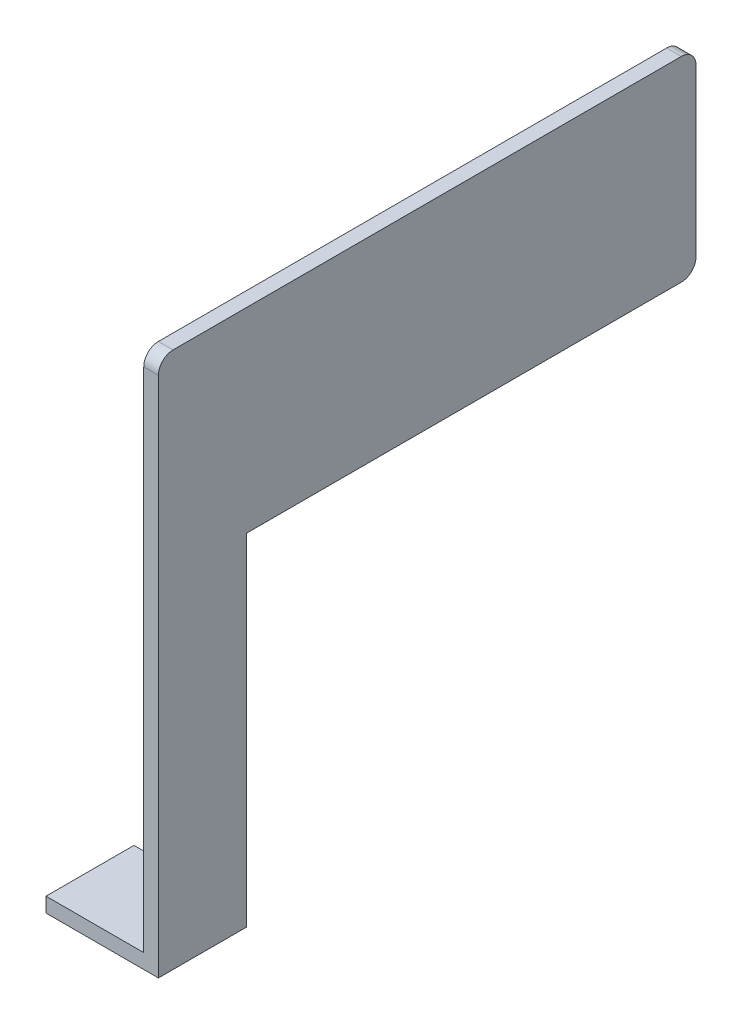
SolidWorks part; units mm, degrees
ref_plane "前视基准面" through (0, 0, 0) normal (0, 0, 1) x (1, 0, 0)
ref_plane "上视基准面" through (0, 0, 0) normal (0, 1, 0) x (1, 0, 0)
ref_plane "右视基准面" through (0, 0, 0) normal (1, 0, 0) x (0, 0, -1)
sketch "草图1" plane through (0, 0, 0) normal (1, 0, 0) x (0, 0, -1)
  line L0 (-5.8, 0) -> (5.8, 0) construction
  line L2 (-5.5, -2) -> (-5.5, -1.5)
  line L3 (-5.5, 2) -> (5.5, 2)
  line L4 (5.5, -2) -> (5.5, -1.5)
  line L5 (-5.5, -2) -> (5.5, 2) construction
  line L6 (-5.5, 2) -> (5.5, -2) construction
  line L10 (-5.5, 1.5) -> (-5.5, 0.5)
  line L11 (0, 2) -> (0, -2) construction
  line L12 (-5.5, 1.5) -> (-5.5, 2)
  line L15 (-5.5, -1.5) -> (-5.5, -0.5)
  line L17 (5.5, 1.5) -> (5.5, 0.5)
  line L20 (5.5, -1.5) -> (5.5, -0.5)
  line L22 (5.5, 1.5) -> (5.5, 2)
  line L23 (5.5, -0.5) -> (5.5, 0.5)
  line L24 (-5.5, -0.5) -> (-5.5, 0.5)
  line L25 (-3.7, -2) -> (5.5, -2)
  line L30 (-5.5, -2) -> (-5.5, -8.98)
  line L31 (-5.5, -8.98) -> (-3.7, -8.98)
  line L32 (-3.7, -8.98) -> (-3.7, -2)
  point P0 (0, 0)
  dimension "D1" = 11
  dimension "D2" = 4
  dimension "D6" = 1.8
  dimension "D7" = 6.98
extrude "凸台-拉伸1" add sketch "草图1" along normal blind 0.3
sketch "草图3" plane through (0, 0, 0) normal (-1, 0, 0) x (0, 0, 1)
  line L0 (5.5, 2) -> (5.5, -8.98) construction
  line L1 (3.7, -8.98) -> (5.5, -8.98)
  line L2 (3.7, -8.98) -> (3.7, -8.68)
  line L3 (3.7, -8.68) -> (5.5, -8.68)
  line L4 (5.5, -8.98) -> (5.5, -8.68)
  dimension "D1" = 0.3
extrude "凸台-拉伸2" add sketch "草图3" along normal blind 2
fillet "圆角1" radius 0.3 3 edges at (0.15, -2, -5.5) (0.15, 2, -5.5) (0.15, 2, 5.5)
